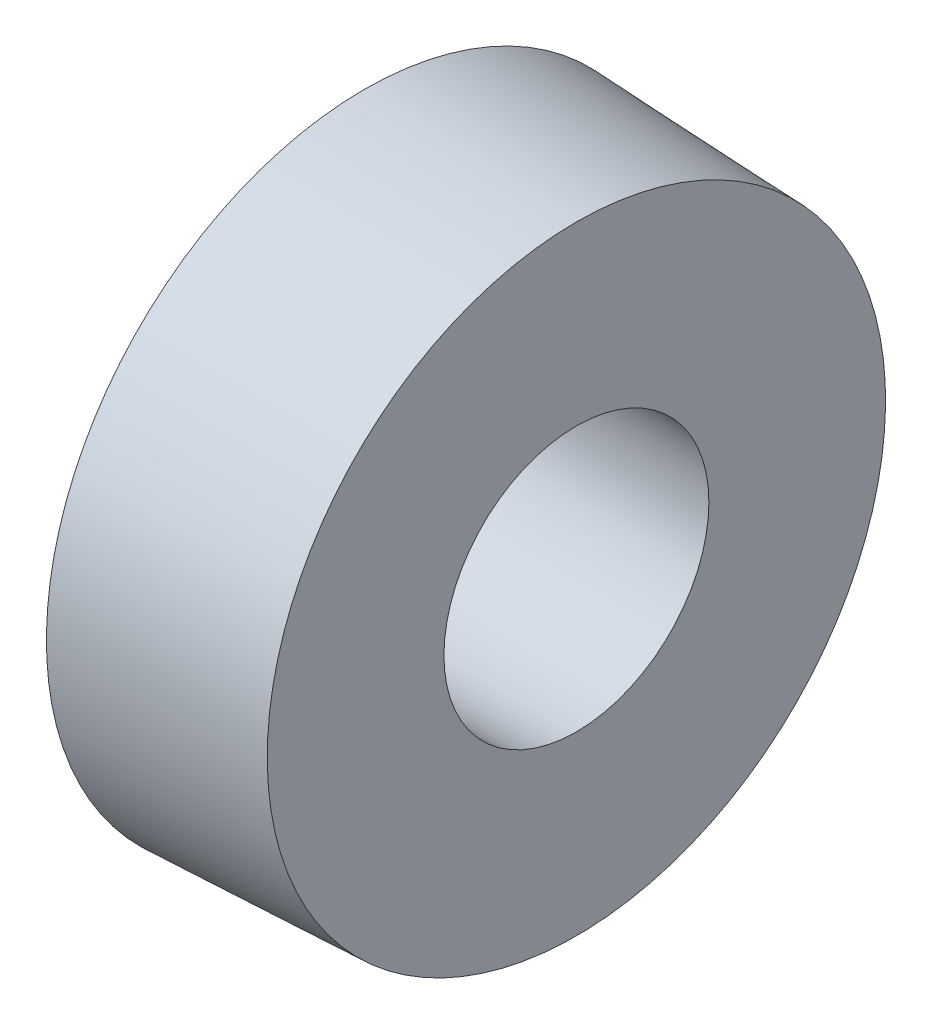
SolidWorks part; units mm, degrees
ref_plane "Front Plane" through (0, 0, 0) normal (0, 0, 1) x (1, 0, 0)
ref_plane "Top Plane" through (0, 0, 0) normal (0, 1, 0) x (1, 0, 0)
ref_plane "Right Plane" through (0, 0, 0) normal (1, 0, 0) x (0, 0, -1)
sketch "Sketch1" plane through (0, 0, 0) normal (0, 0, 1) x (1, 0, 0)
  line L0 (0, 0) -> (8000, 0) construction
  line L1 (6120, 300) -> (6120, 720)
  line L2 (6120, 720) -> (6600, 700)
  line L3 (6600, 700) -> (6600, 300)
  line L4 (6600, 300) -> (6120, 300)
revolve "Revolve1" add sketch "Sketch1" angle 360 about L0
